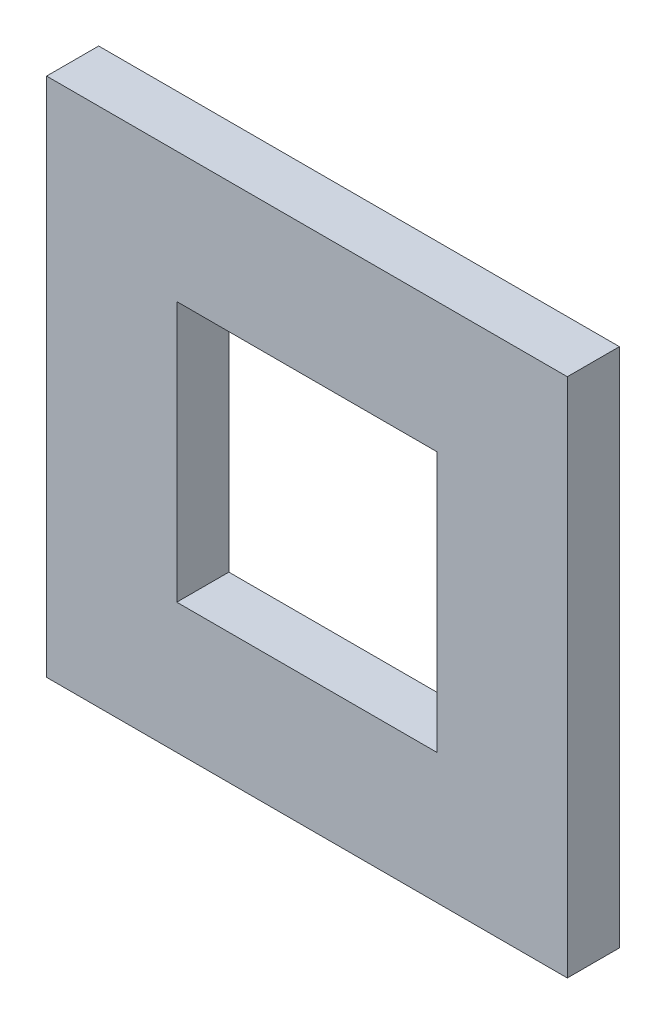
SolidWorks part; units mm, degrees
ref_plane "Front Plane" through (0, 0, 0) normal (0, 0, 1) x (1, 0, 0)
ref_plane "Top Plane" through (0, 0, 0) normal (0, 1, 0) x (1, 0, 0)
ref_plane "Right Plane" through (0, 0, 0) normal (1, 0, 0) x (0, 0, -1)
sketch "Sketch1" plane through (0, 0, 0) normal (0, 0, 1) x (1, 0, 0)
  line L1 (-12.5, -12.5) -> (12.5, -12.5)
  line L2 (-12.5, -12.5) -> (-12.5, 12.5)
  line L3 (-12.5, 12.5) -> (12.5, 12.5)
  line L4 (12.5, -12.5) -> (12.5, 12.5)
  line L5 (-12.5, -12.5) -> (12.5, 12.5) construction
  line L6 (-12.5, 12.5) -> (12.5, -12.5) construction
  point P0 (0, 0)
  dimension "D1" = 25
  dimension "D2" = 25
extrude "Boss-Extrude1" add sketch "Sketch1" along normal blind 2.5
sketch "Sketch2" plane through (0, 0, 2.5) normal (0, 0, 1) x (1, 0, 0)
  line L1 (-6.25, -6.25) -> (6.25, -6.25)
  line L2 (-6.25, -6.25) -> (-6.25, 6.25)
  line L3 (-6.25, 6.25) -> (6.25, 6.25)
  line L4 (6.25, -6.25) -> (6.25, 6.25)
  line L5 (-6.25, -6.25) -> (6.25, 6.25) construction
  line L6 (-6.25, 6.25) -> (6.25, -6.25) construction
  point P0 (0, 0)
  dimension "D1" = 12.5
  dimension "D2" = 12.5
extrude "Cut-Extrude1" cut sketch "Sketch2" against normal blind 2.5
equation "\"D2@Sketch2\"=\"D1@Sketch2\""
equation "\"D2@Sketch1\"=\"D1@Sketch1\""
